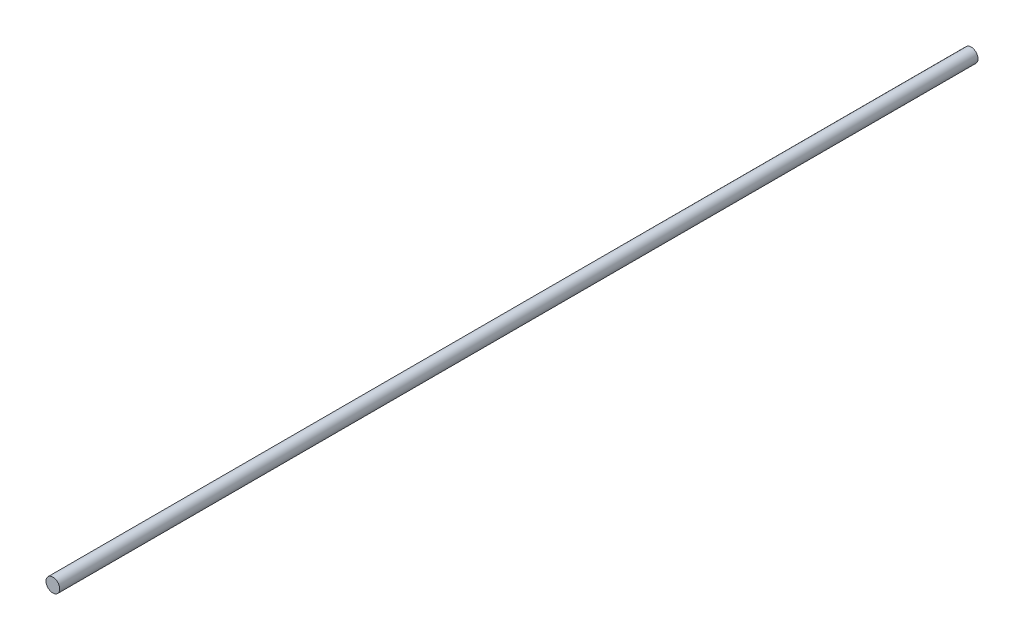
SolidWorks part; units mm, degrees
ref_plane "Front Plane" through (0, 0, 0) normal (0, 0, 1) x (1, 0, 0)
ref_plane "Top Plane" through (0, 0, 0) normal (0, 1, 0) x (1, 0, 0)
ref_plane "Right Plane" through (0, 0, 0) normal (1, 0, 0) x (0, 0, -1)
sketch "Sketch2" plane through (0, 0, 0) normal (0, 0, 1) x (1, 0, 0)
  circle A0 centre (0, 0) radius 15
  dimension "D1" = 30
extrude "Boss-Extrude1" add sketch "Sketch2" along normal blind 2000
